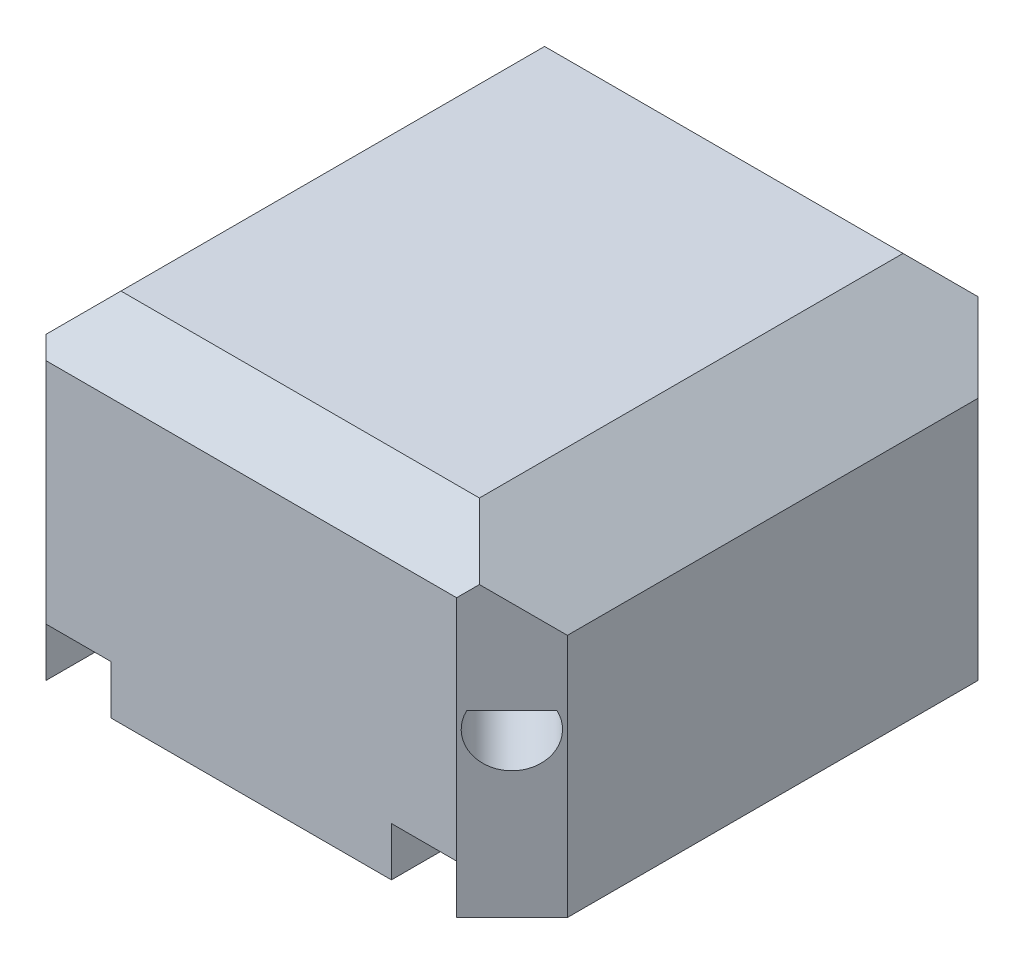
SolidWorks part; units mm, degrees
ref_plane "Front Plane" through (0, 0, 0) normal (0, 0, 1) x (1, 0, 0)
ref_plane "Top Plane" through (0, 0, 0) normal (0, 1, 0) x (1, 0, 0)
ref_plane "Right Plane" through (0, 0, 0) normal (1, 0, 0) x (0, 0, -1)
other "Configuration Table"
sketch "Sketch1" plane through (0, 0, 0) normal (0, 1, 0) x (1, 0, 0)
  line L1 (-175.3431, 76.0713) -> (-15.3431, 76.0713)
  line L2 (-175.3431, 76.0713) -> (-175.3431, -83.9287)
  line L3 (-175.3431, -83.9287) -> (-15.3431, -83.9287)
  line L4 (-15.3431, 76.0713) -> (-15.3431, -83.9287)
extrude "Boss-Extrude1" add sketch "Sketch1" along normal blind 100
chamfer "Chamfer1" distance 25 angle 45 2 edges at (-175.3431, 100, 3.9287) (-15.3431, 100, 3.9287)
chamfer "Chamfer2" distance 17 angle 45 4 edges at (-15.3431, 37.5, -76.0713) (-15.3431, 37.5, 83.9287) (-175.3431, 37.5, -76.0713) (-175.3431, 37.5, 83.9287)
chamfer "Chamfer3" distance 15 angle 45 2 edges at (-95.3431, 100, 83.9287) (-95.3431, 100, -76.0713)
sketch "Sketch2" plane through (21.8641, 0, -21.8641) normal (0.7071, 0, -0.7071) x (-0.7071, 0, -0.7071)
  line L0 (64.6699, 50) -> (64.6699, 55)
  line L1 (71.7108, 100) -> (149.4925, 100) construction
  line L2 (76.6605, 100) -> (76.6605, 0) construction
  line L3 (76.6605, 0) -> (56.1544, 100) construction
  line L4 (-20.2131, 100) -> (71.7108, 100) construction
  line L5 (76.6605, 0) -> (52.6189, 0) construction
  line L7 (74.4678, 55) -> (54.8719, 55)
  circle A0 centre (64.6699, 50) radius 11
  point P14 (64.6397, 0)
  dimension "D1" = 22
  dimension "D2" = 5
  dimension "D3" = 50
extrude "Cut-Extrude1" cut sketch "Sketch2" against normal blind 50
ref_plane "Plane1" through (-95.3431, 0, 0) normal (-1, 0, 0) x (0, 0, 1)
ref_plane "Plane2" through (0, 0, 3.9287) normal (0, 0, -1) x (-1, 0, 0)
sketch "Sketch3" plane through (0, 0, 0) normal (0, -1, 0) x (1, 0, 0)
  line L0 (-32.3431, -76.0713) -> (-158.3431, -76.0713) construction
  line L1 (-158.3431, 83.9287) -> (-138.3431, 83.9287)
  line L2 (-158.3431, 83.9287) -> (-158.3431, -76.0713)
  line L3 (-158.3431, -76.0713) -> (-138.3431, -76.0713)
  line L4 (-138.3431, 83.9287) -> (-138.3431, -76.0713)
  line L6 (-32.3431, 83.9287) -> (-52.3431, 83.9287)
  line L7 (-32.3431, 83.9287) -> (-32.3431, -76.0713)
  line L8 (-32.3431, -76.0713) -> (-52.3431, -76.0713)
  line L9 (-52.3431, 83.9287) -> (-52.3431, -76.0713)
  point P12 (-54.503, 83.9287)
extrude "Cut-Extrude2" cut sketch "Sketch3" against normal blind 15
mirror "Mirror1" about plane through (0, 0, 3.9287) normal (0, 0, -1) of "Cut-Extrude1" second plane through (-95.3431, 0, 0) second plane normal (-1, 0, 0)
